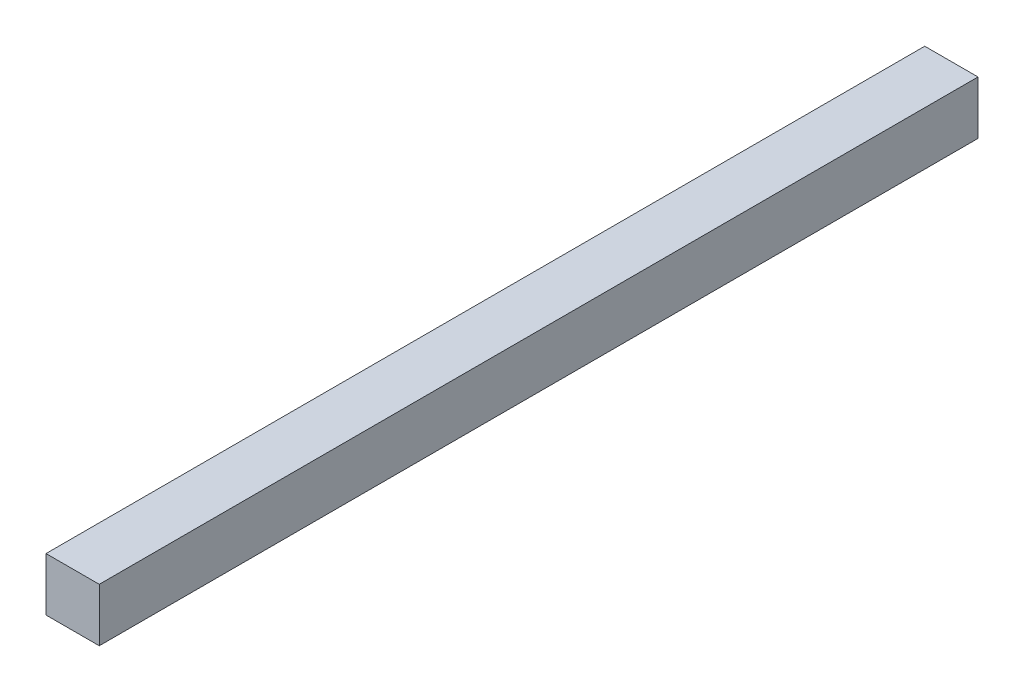
SolidWorks part; units mm, degrees
ref_plane "前视基准面" through (0, 0, 0) normal (0, 0, 1) x (1, 0, 0)
ref_plane "上视基准面" through (0, 0, 0) normal (0, 1, 0) x (1, 0, 0)
ref_plane "右视基准面" through (0, 0, 0) normal (1, 0, 0) x (0, 0, -1)
other "Configuration Table"
sketch "草图1" plane through (0, 0, 0) normal (0, 0, 1) x (1, 0, 0)
  line L1 (0, 0) -> (-20, 0)
  line L2 (0, 0) -> (0, 20)
  line L3 (0, 20) -> (-20, 20)
  line L4 (-20, 0) -> (-20, 20)
  dimension "D1" = 20
  dimension "D2" = 20
extrude "凸台-拉伸1" add sketch "草图1" along normal blind 330
